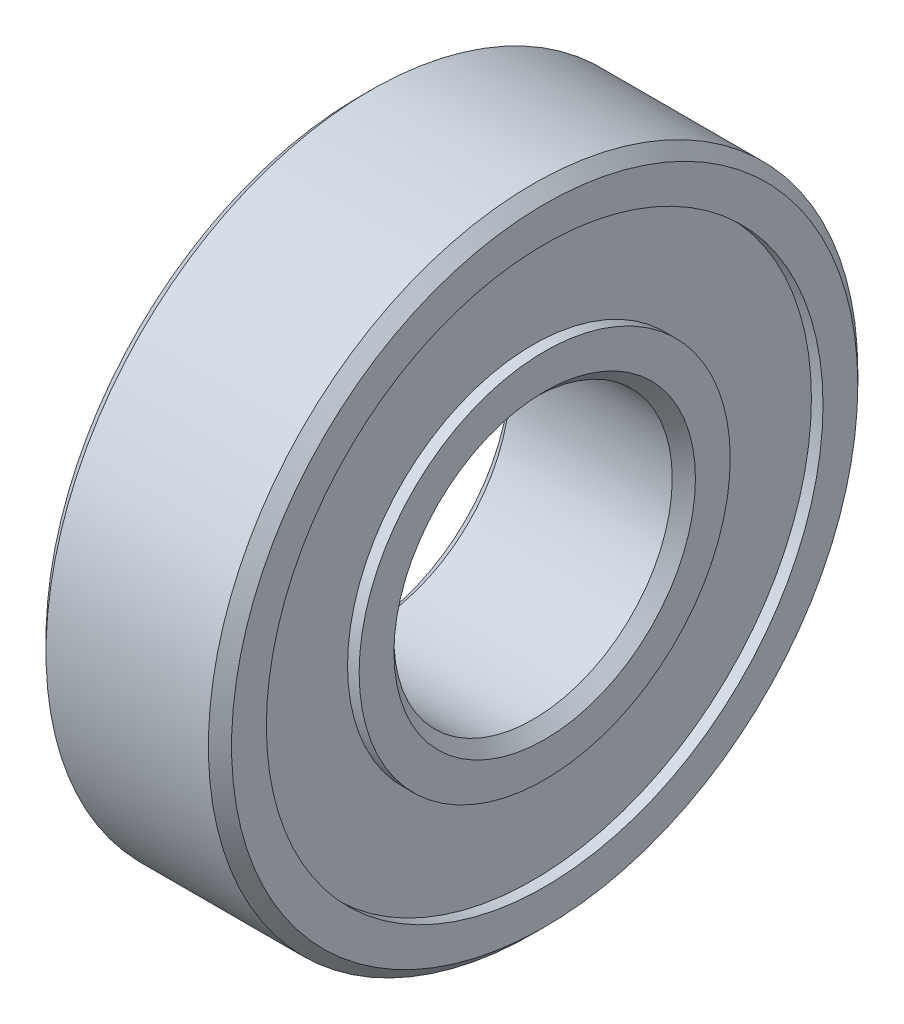
SolidWorks part; units mm, degrees
ref_plane "Front Plane" through (0, 0, 0) normal (0, 0, 1) x (1, 0, 0)
ref_plane "Top Plane" through (0, 0, 0) normal (0, 1, 0) x (1, 0, 0)
ref_plane "Right Plane" through (0, 0, 0) normal (1, 0, 0) x (0, 0, -1)
sketch "Sketch1" plane through (0, 0, 0) normal (1, 0, 0) x (0, 0, -1)
  circle A0 centre (0, 0) radius 6
  circle A1 centre (0, 0) radius 8
  circle A2 centre (0, 0) radius 14
  circle A3 centre (0, 0) radius 12
  dimension "D1" = 28
  dimension "D2" = 12
  dimension "D3" = 2
  dimension "D4" = 2
extrude "Boss-Extrude1" add sketch "Sketch1" along normal mid plane 8 contours A2 A3 | A1 A0
sketch "Sketch2" plane through (0, 0, 0) normal (-1, 0, 0) x (0, 0, 1)
  circle A0 centre (0, 0) radius 8
  circle A1 centre (0, 0) radius 12
extrude "Boss-Extrude2" add sketch "Sketch2" against normal mid plane 7 separate body
chamfer "Chamfer1" distance 0.5 angle 45 2 edges at (4, 0, -14) (-4, 0, -14)
chamfer "Chamfer2" distance 0.5 angle 45 2 edges at (4, 0, -6) (-4, 0, -6)
